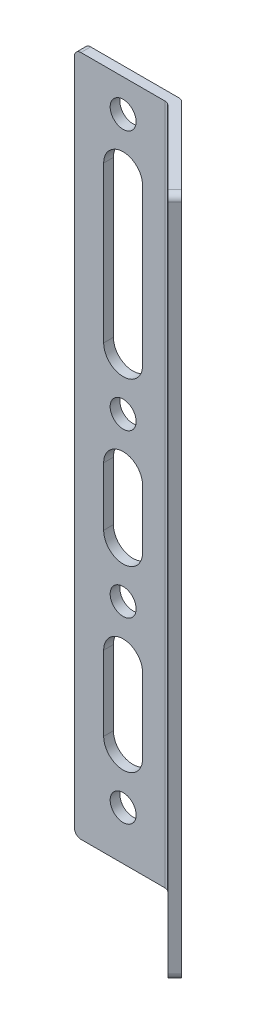
SolidWorks part; units mm, degrees
material "6061 合金"
ref_plane "前视基准面" through (0, 0, 0) normal (0, 0, 1) x (1, 0, 0)
ref_plane "上视基准面" through (0, 0, 0) normal (0, 1, 0) x (1, 0, 0)
ref_plane "右视基准面" through (0, 0, 0) normal (1, 0, 0) x (0, 0, -1)
sketch "草图1" plane through (0, 0, 0) normal (0, 1, 0) x (1, 0, 0)
  line L0 (-15, 0) -> (0, 0)
  line L1 (0, 0) -> (12.7279, -12.7279)
  dimension "D1" = 15
  dimension "D2" = 18
  dimension "D3" = 135
extrude "拉伸-薄壁1" add sketch "草图1" along normal blind 105 thin
sketch "草图2" plane through (0, 0, 1.5) normal (0, 0, 1) x (1, 0, 0)
  line L0 (-15, 105) -> (-15, 0) construction
  line L1 (-15, 105) -> (-0.6213, 105) construction
  line L2 (-15, 0) -> (-0.6213, 0) construction
  line L4 (-7.5, 92) -> (-7.5, 68) construction
  line L5 (-4.5, 92) -> (-4.5, 68)
  line L6 (-10.5, 92) -> (-10.5, 68)
  line L7 (-7.5, 52) -> (-7.5, 43) construction
  line L8 (-4.5, 52) -> (-4.5, 43)
  line L9 (-10.5, 52) -> (-10.5, 43)
  line L10 (-7.5, 27) -> (-7.5, 15.5) construction
  line L11 (-4.5, 27) -> (-4.5, 15.5)
  line L12 (-10.5, 27) -> (-10.5, 15.5)
  circle A0 centre (-7.5, 100) radius 2
  circle A1 centre (-7.5, 60) radius 2
  circle A2 centre (-7.5, 35) radius 2
  circle A3 centre (-7.5, 7.5) radius 2
  arc A4 (-4.5, 92) -> (-10.5, 92) centre (-7.5, 92) ccw
  arc A5 (-10.5, 68) -> (-4.5, 68) centre (-7.5, 68) ccw
  arc A6 (-4.5, 52) -> (-10.5, 52) centre (-7.5, 52) ccw
  arc A7 (-10.5, 43) -> (-4.5, 43) centre (-7.5, 43) ccw
  arc A8 (-4.5, 27) -> (-10.5, 27) centre (-7.5, 27) ccw
  arc A9 (-10.5, 15.5) -> (-4.5, 15.5) centre (-7.5, 15.5) ccw
  point P6 (0, 0)
  point P7 (0, 0)
  point P10 (0, 0)
  point P11 (0, 0)
  point P16 (-7.5, 80)
  point P23 (-7.5, 47.5)
  point P30 (-7.5, 21.25)
  point P39 (-7.5, 12.5)
  point P40 (-7.5, 30)
  point P41 (-7.5, 40)
  point P42 (-7.5, 55)
  point P43 (-7.5, 65)
  point P44 (-7.5, 95)
  dimension "D1" = 4
  dimension "D2" = 5
  dimension "D3" = 40
  dimension "D4" = 25
  dimension "D6" = 7.5
  dimension "D10" = 5
  dimension "D5" = 7.5
  dimension "D7" = 5
  dimension "D8" = 5
  dimension "D9" = 6
  dimension "D11" = 5
  dimension "D12" = 5
  dimension "D13" = 5
extrude "切除-拉伸1" cut sketch "草图2" against normal through all
sketch "草图3" plane through (11.6673, 0, 13.7886) normal (-0.7071, 0, 0.7071) x (0.7071, 0, 0.7071)
  line L0 (0, 105) -> (0, 0) construction
  line L1 (-17.3787, 0) -> (0, 0) construction
  line L4 (-7.5, 92) -> (-7.5, 68) construction
  line L5 (-4.5, 92) -> (-4.5, 68)
  line L6 (-10.5, 92) -> (-10.5, 68)
  line L7 (-7.5, 52) -> (-7.5, 43) construction
  line L8 (-4.5, 52) -> (-4.5, 43)
  line L9 (-10.5, 52) -> (-10.5, 43)
  line L10 (-7.5, 27) -> (-7.5, 15.5) construction
  line L11 (-4.5, 27) -> (-4.5, 15.5)
  line L12 (-10.5, 27) -> (-10.5, 15.5)
  circle A0 centre (-7.5, 100) radius 2
  circle A1 centre (-7.5, 60) radius 2
  circle A2 centre (-7.5, 35) radius 2
  circle A3 centre (-7.5, 7.5) radius 2
  arc A4 (-4.5, 92) -> (-10.5, 92) centre (-7.5, 92) ccw
  arc A5 (-10.5, 68) -> (-4.5, 68) centre (-7.5, 68) ccw
  arc A6 (-4.5, 52) -> (-10.5, 52) centre (-7.5, 52) ccw
  arc A7 (-10.5, 43) -> (-4.5, 43) centre (-7.5, 43) ccw
  arc A8 (-4.5, 27) -> (-10.5, 27) centre (-7.5, 27) ccw
  arc A9 (-10.5, 15.5) -> (-4.5, 15.5) centre (-7.5, 15.5) ccw
  point P6 (0, 0)
  point P7 (0, 0)
  point P10 (0, 0)
  point P11 (0, 0)
  point P16 (-7.5, 80)
  point P23 (-7.5, 47.5)
  point P30 (-7.5, 21.25)
  dimension "D1" = 7.5
  dimension "D2" = 7.5
extrude "切除-拉伸2" cut sketch "草图3" against normal through all
fillet "圆角1" radius 1 6 edges at (-0.6213, 52.5, 1.5) (0, 52.5, 0) (-15, 105, 0.75) (12.1976, 105, 13.2583) (-15, 0, 0.75) (12.1976, 0, 13.2583)
